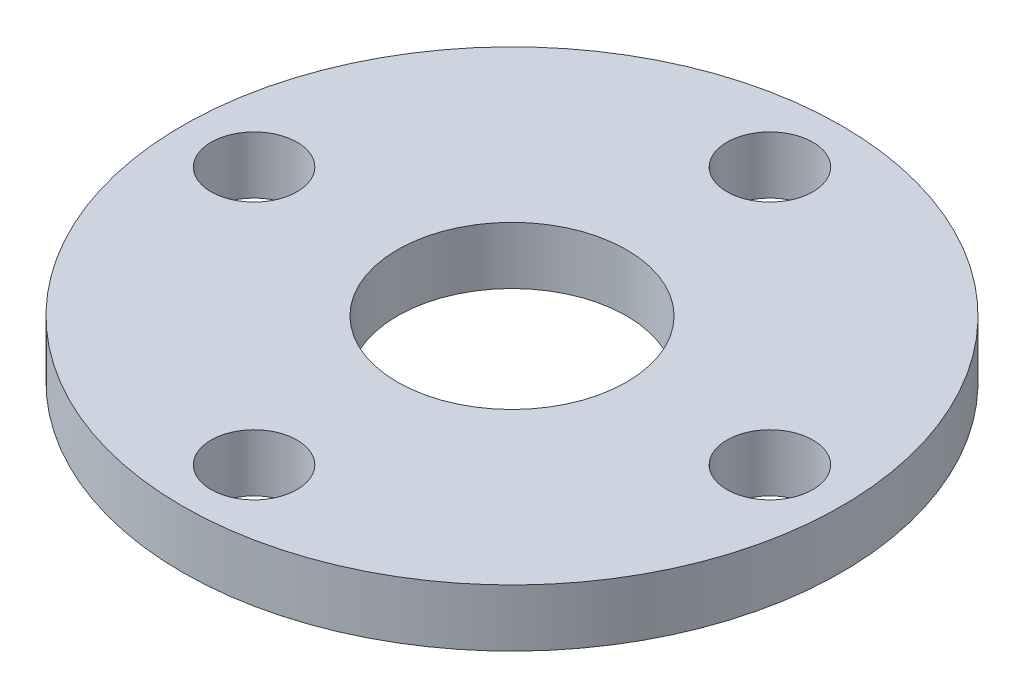
SolidWorks part; units mm, degrees
ref_plane "Front Plane" through (0, 0, 0) normal (0, 0, 1) x (1, 0, 0)
ref_plane "Top Plane" through (0, 0, 0) normal (0, 1, 0) x (1, 0, 0)
ref_plane "Right Plane" through (0, 0, 0) normal (1, 0, 0) x (0, 0, -1)
sketch "Sketch1" plane through (0, 0, 0) normal (0, 1, 0) x (1, 0, 0)
  line L0 (0, 0) -> (-9, 0) construction
  line L1 (0, 0) -> (0, 9) construction
  line L2 (0, 0) -> (9, 0) construction
  line L3 (0, 0) -> (0, -9) construction
  circle A0 centre (0, 0) radius 4
  circle A1 centre (0, 0) radius 11.5
  circle A2 centre (9, 0) radius 1.5
  circle A3 centre (0, 9) radius 1.5
  circle A4 centre (-9, 0) radius 1.5
  circle A5 centre (0, -9) radius 1.5
extrude "Boss-Extrude1" add sketch "Sketch1" along normal blind 2
